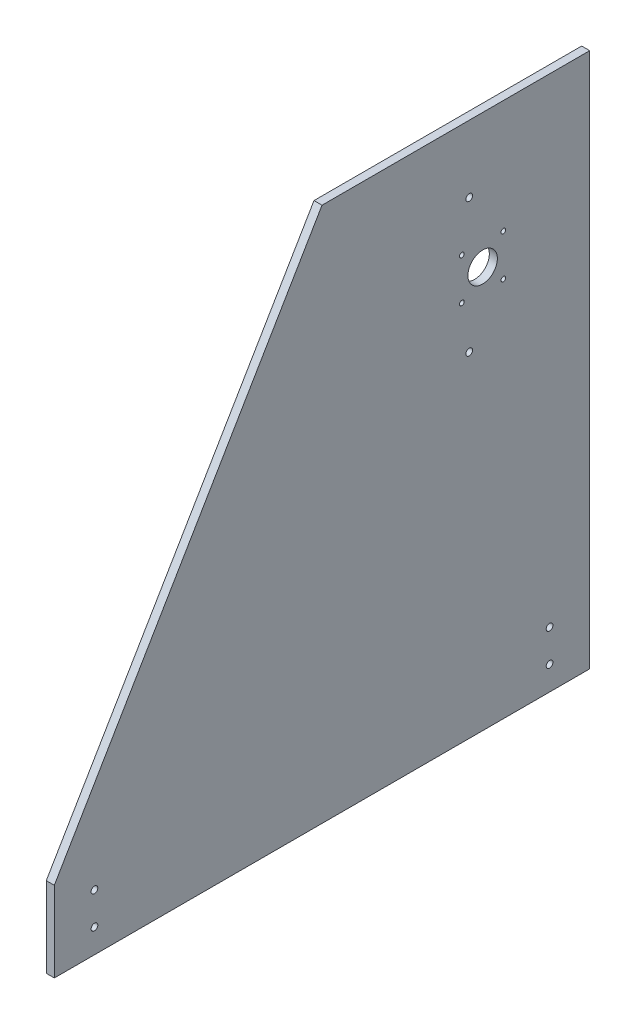
SolidWorks part; units mm, degrees
ref_plane "Front Plane" through (0, 0, 0) normal (0, 0, 1) x (1, 0, 0)
ref_plane "Top Plane" through (0, 0, 0) normal (0, 1, 0) x (1, 0, 0)
ref_plane "Right Plane" through (0, 0, 0) normal (1, 0, 0) x (0, 0, -1)
sketch "Sketch1" plane through (0, 0, 0) normal (1, 0, 0) x (0, 0, -1)
  line L0 (0, -2343.7616) -> (0, 114844.3172) construction
  line L1 (-2343.7616, 0) -> (114844.3172, 0) construction
  line L2 (0, 60) -> (400, 60) construction
  line L3 (0, 0) -> (400, 0)
  line L5 (200, 400) -> (400, 400)
  line L6 (400, 0) -> (400, 400)
  line L7 (0, 60) -> (200, 400)
  line L8 (0, 60) -> (0, 0)
  line L9 (-1000, 30) -> (49000, 30) construction
  line L10 (200, -1000) -> (200, 49000) construction
  line L11 (310, -1000) -> (310, 49000) construction
  line L12 (320, -1008.4066) -> (320, 48991.5934) construction
  line L13 (298.2689, 300) -> (341.7311, 300) construction
  circle A0 centre (30, 42) radius 2.5
  circle A2 centre (30, 18) radius 2.5
  circle A3 centre (370, 18) radius 2.5
  circle A4 centre (370, 42) radius 2.5
  circle A5 centre (310, 350) radius 2.5
  circle A6 centre (310, 250) radius 2.5
  circle A7 centre (320, 300) radius 11
  circle A8 centre (335.5, 315.5) radius 1.75
  circle A9 centre (304.5, 315.5) radius 1.75
  circle A10 centre (304.5, 284.5) radius 1.75
  circle A11 centre (335.5, 284.5) radius 1.75
  point P14 (0, 30)
  point P21 (200, 0)
  point P38 (320, 300)
  point P42 (336.0127, 300)
  dimension "D7" = 5
  dimension "D9" = 5
  dimension "D14" = 22
  dimension "D16" = 15.5
  dimension "D17" = 3.5
  dimension "D1" = 400
  dimension "D2" = 400
  dimension "D3" = 60
  dimension "D4" = 200
  dimension "D5" = 30
  dimension "D6" = 90
  dimension "D8" = 12
  dimension "D10" = 50
  dimension "D11" = 100
  dimension "D12" = 80
  dimension "D13" = 50
  dimension "D15" = 15.5
extrude "Boss-Extrude1" add sketch "Sketch1" along normal blind 6
